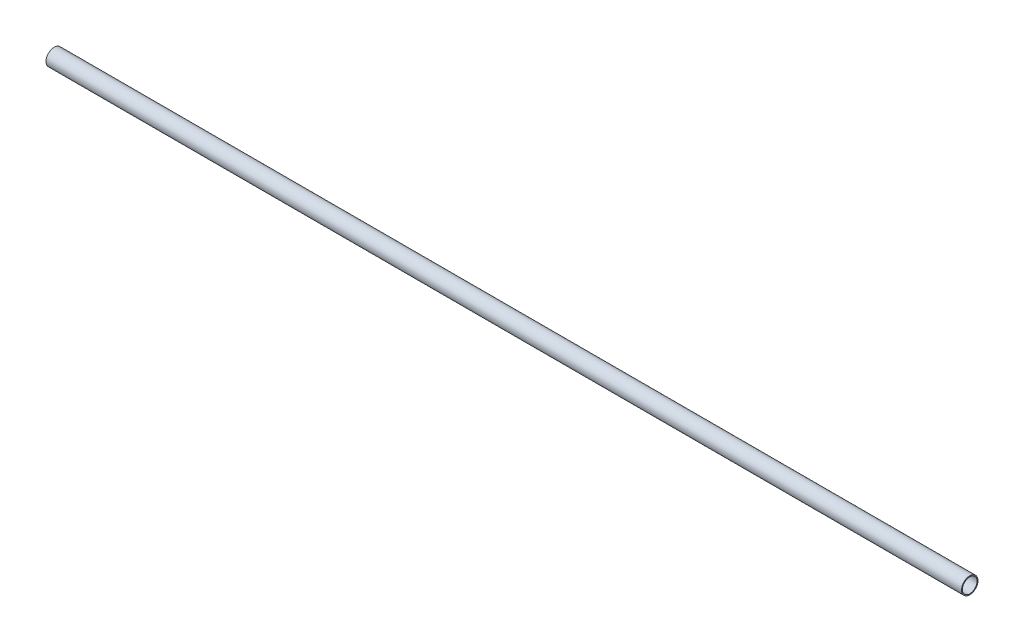
SolidWorks part; units mm, degrees
material "windcatcher"
ref_plane "Front Plane" through (0, 0, 0) normal (0, 0, 1) x (1, 0, 0)
ref_plane "Top Plane" through (0, 0, 0) normal (0, 1, 0) x (1, 0, 0)
ref_plane "Right Plane" through (0, 0, 0) normal (1, 0, 0) x (0, 0, -1)
sketch "Sketch1" plane through (0, 0, 0) normal (1, 0, 0) x (0, 0, -1)
  circle A0 centre (0, 0) radius 9
  circle A1 centre (0, 0) radius 8
  dimension "D1" = 18
  dimension "D2" = 16
extrude "Boss-Extrude1" add sketch "Sketch1" along normal mid plane 1000
